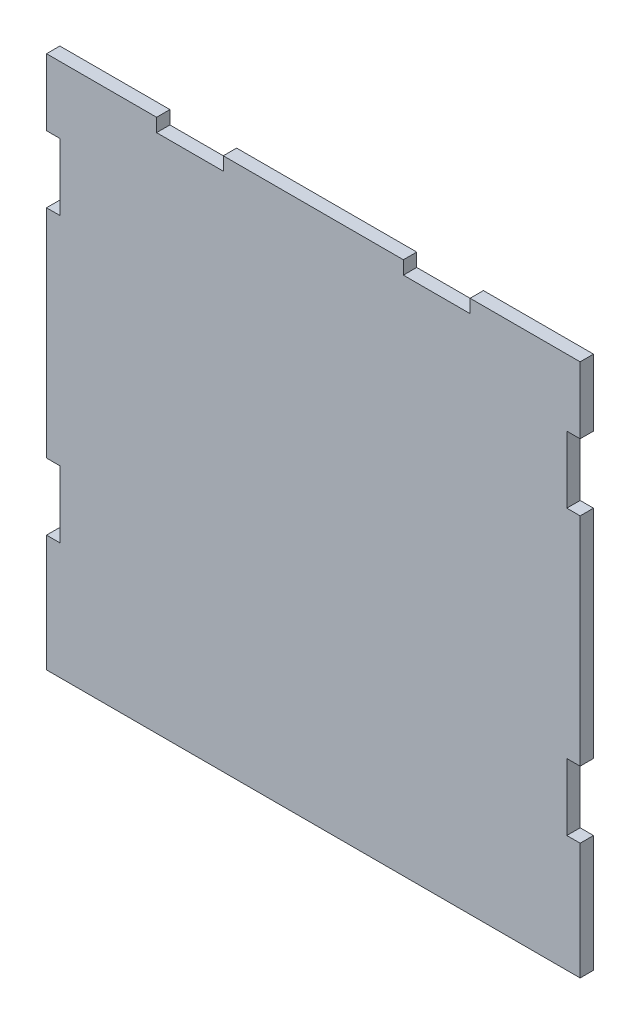
SolidWorks part; units mm, degrees
ref_plane "Front Plane" through (0, 0, 0) normal (0, 0, 1) x (1, 0, 0)
ref_plane "Top Plane" through (0, 0, 0) normal (0, 1, 0) x (1, 0, 0)
ref_plane "Right Plane" through (0, 0, 0) normal (1, 0, 0) x (0, 0, -1)
sketch "Sketch1" plane through (0, 0, 0) normal (0, 0, 1) x (1, 0, 0)
  line L0 (-101.6, 0) -> (101.6, 0)
  line L1 (-101.6, 101.6) -> (101.6, 101.6)
  line L2 (-101.6, 101.6) -> (-101.6, -101.6)
  line L3 (-101.6, -101.6) -> (101.6, -101.6)
  line L4 (101.6, 101.6) -> (101.6, -101.6)
  point P6 (0, 0)
  dimension "D1" = 203.2
  dimension "D2" = 203.2
extrude "Boss-Extrude1" add sketch "Sketch1" along normal blind 5.08 contours L4 L1 L2 L0 | L4 L0 L2 L3
sketch "Sketch2" plane through (0, 0, 0) normal (0, 0, -1) x (-1, 0, 0)
  line L0 (101.6, 101.6) -> (101.6, -101.6) construction
  line L1 (101.6, -57.15) -> (96.52, -57.15)
  line L2 (101.6, -57.15) -> (101.6, -31.75)
  line L3 (101.6, -31.75) -> (96.52, -31.75)
  line L4 (96.52, -57.15) -> (96.52, -31.75)
  line L5 (101.6, 101.6) -> (-101.6, 101.6) construction
  line L6 (101.6, 50.8) -> (96.52, 50.8)
  line L7 (101.6, 50.8) -> (101.6, 76.2)
  line L8 (101.6, 76.2) -> (96.52, 76.2)
  line L9 (96.52, 50.8) -> (96.52, 76.2)
  line L10 (59.69, 101.6) -> (34.29, 101.6)
  line L11 (59.69, 101.6) -> (59.69, 96.52)
  line L12 (59.69, 96.52) -> (34.29, 96.52)
  line L13 (34.29, 101.6) -> (34.29, 96.52)
  line L14 (-101.6, 101.6) -> (-101.6, -101.6) construction
  line L15 (-34.29, 101.6) -> (-59.69, 101.6)
  line L16 (-34.29, 101.6) -> (-34.29, 96.52)
  line L17 (-34.29, 96.52) -> (-59.69, 96.52)
  line L18 (-59.69, 101.6) -> (-59.69, 96.52)
  line L19 (101.6, -101.6) -> (101.6, -57.15)
  line L20 (-101.6, 76.2) -> (-96.52, 76.2)
  line L21 (-101.6, 76.2) -> (-101.6, 50.8)
  line L22 (-101.6, 50.8) -> (-96.52, 50.8)
  line L23 (-96.52, 76.2) -> (-96.52, 50.8)
  line L24 (-101.6, -31.75) -> (-96.52, -31.75)
  line L25 (-101.6, -31.75) -> (-101.6, -57.15)
  line L26 (-101.6, -57.15) -> (-96.52, -57.15)
  line L27 (-96.52, -31.75) -> (-96.52, -57.15)
  line L28 (-101.6, -101.6) -> (-101.6, -57.15)
  line L29 (-101.6, 76.2) -> (-101.6, 101.6)
  line L30 (-101.6, 101.6) -> (-59.69, 101.6)
  line L31 (59.69, 101.6) -> (101.6, 101.6)
  line L32 (101.6, 101.6) -> (101.6, 76.2)
  line M23 (-101.6, 101.6) -> (-101.6, -101.6)
  line M25 (101.6, -101.6) -> (101.6, 101.6)
  line M26 (101.6, 101.6) -> (-101.6, 101.6)
  dimension "D1" = 5.08
  dimension "D2" = 25.4
  dimension "D3" = 41.91
  dimension "D4" = 25.4
  dimension "D5" = 44.45
extrude "Cut-Extrude1" cut sketch "Sketch2" against normal blind 5.08 contours L27 L24 L26 M23 | L4 L1 L3 M25 | L9 L6 L8 M25 | L13 L12 L11 M26 | L18 L17 L16 M26 | L23 L20 L22 M23
